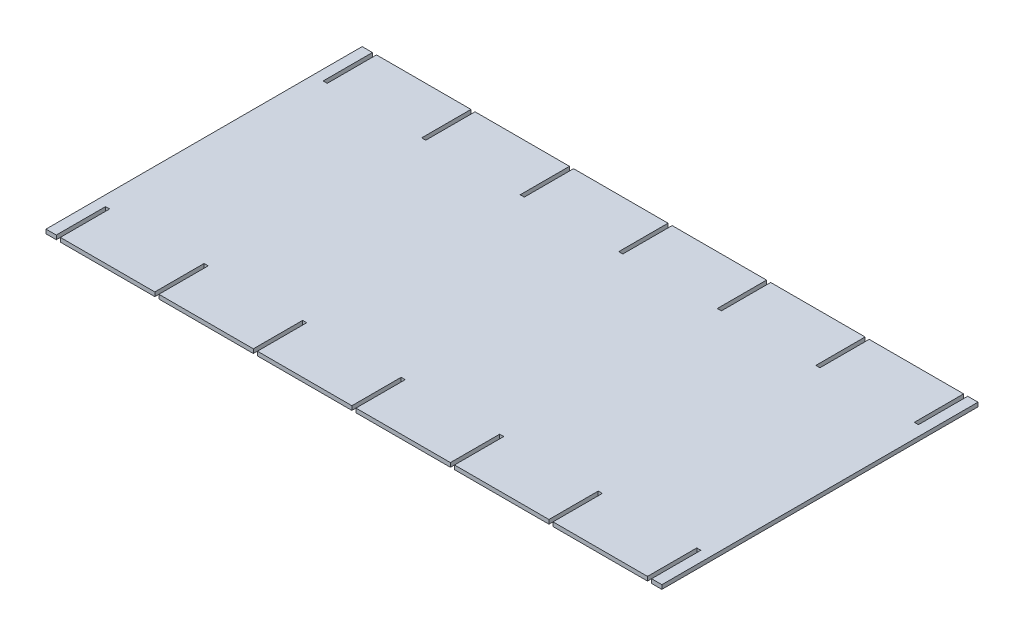
SolidWorks part; units mm, degrees
ref_plane "Front Plane" through (0, 0, 0) normal (0, 0, 1) x (1, 0, 0)
ref_plane "Top Plane" through (0, 0, 0) normal (0, 1, 0) x (1, 0, 0)
ref_plane "Right Plane" through (0, 0, 0) normal (1, 0, 0) x (0, 0, -1)
sketch "Sketch1" plane through (0, 0, 0) normal (0, 1, 0) x (1, 0, 0)
  line L1 (-150, 77) -> (150, 77)
  line L2 (-150, 77) -> (-150, -77)
  line L3 (-150, -77) -> (150, -77)
  line L4 (150, 77) -> (150, -77)
  line L5 (-150, 77) -> (150, -77) construction
  line L6 (-150, -77) -> (150, 77) construction
  point P0 (0, 0)
  dimension "D1" = 154
  dimension "D2" = 300
extrude "Boss-Extrude1" add sketch "Sketch1" along normal blind 2
sketch "Sketch2" plane through (0, 2, 0) normal (0, 1, 0) x (1, 0, 0)
  line L0 (-150, -77) -> (150, -77) construction
  line L1 (-145, -77) -> (-143, -77)
  line L2 (-145, -77) -> (-145, -53)
  line L3 (-145, -53) -> (-143, -53)
  line L4 (-143, -77) -> (-143, -53)
  line L5 (-150, 77) -> (-150, -77) construction
  dimension "D1" = 24
  dimension "D2" = 2
  dimension "D3" = 5
extrude "Cut-Extrude1" cut sketch "Sketch2" against normal up to next
pattern_linear "LPattern1" count 7 spacing 48 along (1, 0, 0) of "Cut-Extrude1"
mirror "Mirror1" about plane through (0, 0, 0) normal (0, 0, 1) of "Cut-Extrude1", "LPattern1"
